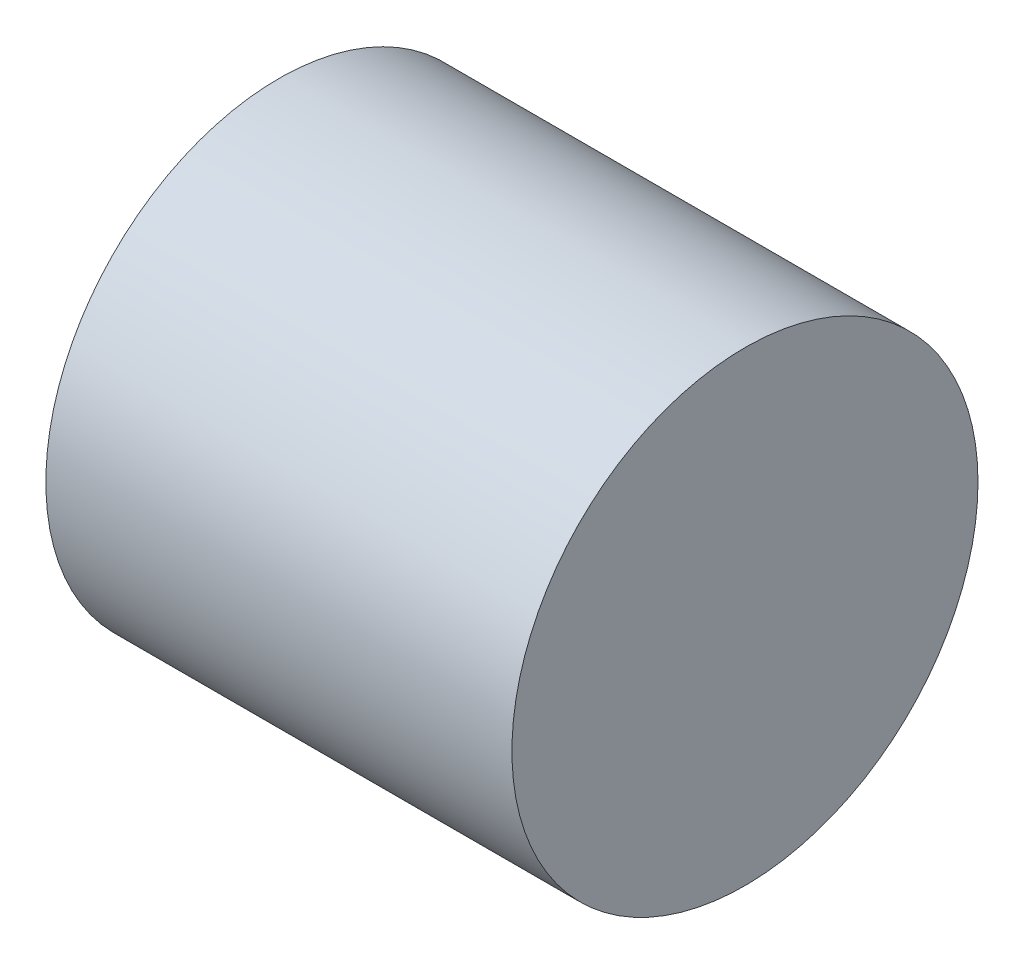
SolidWorks part; units mm, degrees
ref_plane "Plan de face" through (0, 0, 0) normal (0, 0, 1) x (1, 0, 0)
ref_plane "Plan de dessus" through (0, 0, 0) normal (0, 1, 0) x (1, 0, 0)
ref_plane "Plan de droite" through (0, 0, 0) normal (1, 0, 0) x (0, 0, -1)
sketch "Esquisse1" plane through (0, 0, 0) normal (1, 0, 0) x (0, 0, -1)
  circle A0 centre (0, 0) radius 75
  dimension "D1" = 150
extrude "Boss.-Extru.1" add sketch "Esquisse1" along normal blind 150 contours A0
